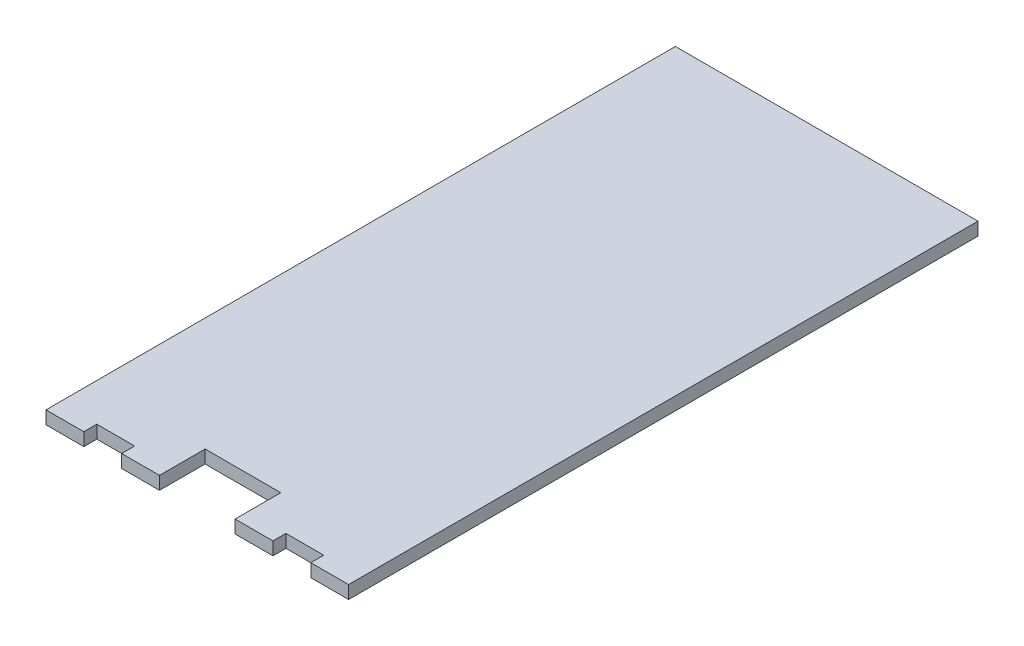
SolidWorks part; units mm, degrees
ref_plane "Front Plane" through (0, 0, 0) normal (0, 0, 1) x (1, 0, 0)
ref_plane "Top Plane" through (0, 0, 0) normal (0, 1, 0) x (1, 0, 0)
ref_plane "Right Plane" through (0, 0, 0) normal (1, 0, 0) x (0, 0, -1)
sketch "Sketch1" plane through (0, 0, 0) normal (0, 1, 0) x (1, 0, 0)
  line L1 (-94.968, 43.1681) -> (99.215, 43.1681)
  line L2 (-94.968, 43.1681) -> (-94.968, -360.7224)
  line L3 (-94.968, -360.7224) -> (99.215, -360.7224)
  line L4 (99.215, 43.1681) -> (99.215, -360.7224)
  dimension "D1" = 403.8905
  dimension "D2" = 194.183
extrude "Boss-Extrude1" add sketch "Sketch1" along normal blind 8.3312
sketch "Sketch2" plane through (0, 0, 0) normal (0, -1, 0) x (1, 0, 0)
  line L0 (-94.968, 360.7224) -> (99.215, 360.7224) construction
  line L1 (-70.6951, 360.7224) -> (-46.4222, 360.7224)
  line L2 (-70.6951, 360.7224) -> (-70.6951, 352.3912)
  line L3 (-70.6951, 352.3912) -> (-46.4222, 352.3912)
  line L4 (-46.4222, 360.7224) -> (-46.4222, 352.3912)
  line L5 (2.1235, 360.7224) -> (2.1235, -43.1681) construction
  line L6 (99.215, -43.1681) -> (-94.968, -43.1681) construction
  line L7 (-94.968, -43.1681) -> (-94.968, 360.7224) construction
  line L8 (26.3964, 360.7224) -> (-22.1494, 360.7224)
  line L9 (2.1235, 360.7224) -> (2.1235, 331.4362)
  line L10 (26.3964, 331.4362) -> (-22.1494, 331.4362)
  line L11 (-22.1494, 360.7224) -> (-22.1494, 331.4362)
  line L12 (26.3964, 360.7224) -> (26.3964, 331.4362)
  line L13 (74.9421, 352.3912) -> (50.6693, 352.3912)
  line L14 (50.6693, 360.7224) -> (50.6693, 352.3912)
  line L15 (74.9421, 360.7224) -> (50.6693, 360.7224)
  line L16 (74.9421, 360.7224) -> (74.9421, 352.3912)
  line M6 (99.215, 360.7224) -> (-94.968, 360.7224)
  dimension "D1" = 8.3312
  dimension "D2" = 29.2862
  dimension "D3" = 24.2729
  dimension "D4" = 24.2729
  dimension "D6" = 24.2729
  dimension "D5" = 24.2729
extrude "Cut-Extrude1" cut sketch "Sketch2" against normal through all contours L4 L2 L3 M6 | L8 L11 L10 L9 | L12 L9 L10 M6 | L16 L14 L13 M6
equation "\"D1@Sketch1\"=\"Side Height@Assembled Container.Assembly\""
equation "\"D2@Sketch1\"=\"Short Side Width@Assembled Container.Assembly\""
equation "\"D1@Boss-Extrude1\"=\"Acrylic Thickness@Assembled Container.Assembly\""
equation "\"D1@Sketch2\"=\"Acrylic Thickness@Assembled Container.Assembly\""
equation "\"D2@Sketch2\" = \"Short Side Finger Hole@Assembled Container.Assembly\""
equation "\"D3@Sketch2\"=\"Lid Short Side Outer Cutout@Assembled Container.Assembly\""
equation "\"D4@Sketch2\"=\"Lid Short Side Outer Overhang@Assembled Container.Assembly\""
equation "\"D5@Sketch2\"=\"Lid Short Side Middle Overhang@Assembled Container.Assembly\""
